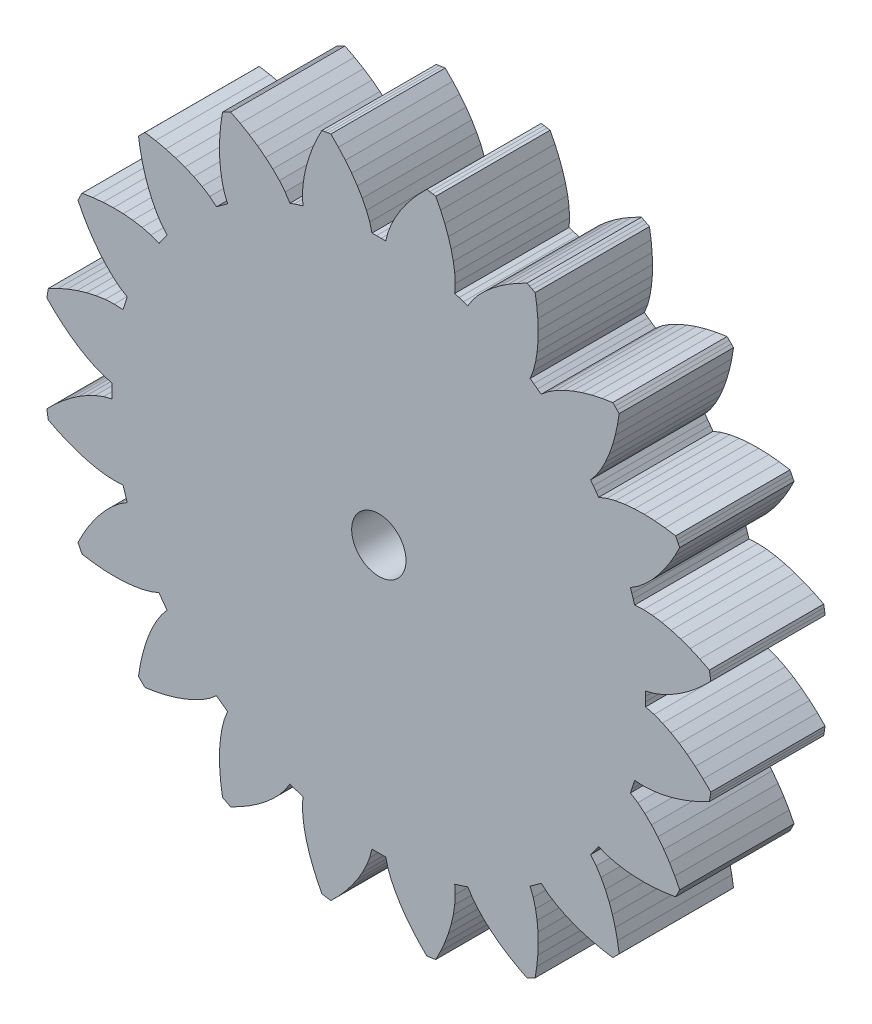
SolidWorks part; units mm, degrees
ref_plane "前视基准面" through (0, 0, 0) normal (0, 0, 1) x (1, 0, 0)
ref_plane "上视基准面" through (0, 0, 0) normal (0, 1, 0) x (1, 0, 0)
ref_plane "右视基准面" through (0, 0, 0) normal (1, 0, 0) x (0, 0, -1)
other "Configuration Table"
sketch "草图1" plane through (0, 0, 0) normal (0, 0, 1) x (1, 0, 0)
  line L0 (34.9884, 0.9021) -> (36.1053, 1.1916)
  line L1 (36.1053, 1.1916) -> (37.2145, 1.6253)
  line L2 (37.2145, 1.6253) -> (38.3134, 2.1726)
  line L3 (38.3134, 2.1726) -> (39.3992, 2.8203)
  line L4 (39.3992, 2.8203) -> (40.4686, 3.5609)
  line L5 (40.4686, 3.5609) -> (41.5186, 4.3893)
  line L6 (41.5186, 4.3893) -> (42.546, 5.3016)
  line L7 (42.546, 5.3016) -> (43.5474, 6.2949)
  line L8 (43.5474, 6.2949) -> (43.4889, 6.6872)
  line L9 (43.4889, 6.6872) -> (43.4268, 7.0789)
  line L10 (43.4268, 7.0789) -> (43.3613, 7.4701)
  line L11 (43.3613, 7.4701) -> (42.1019, 8.1053)
  line L12 (42.1019, 8.1053) -> (40.8429, 8.6555)
  line L13 (40.8429, 8.6555) -> (39.5883, 9.1189)
  line L14 (39.5883, 9.1189) -> (38.3424, 9.4927)
  line L15 (38.3424, 9.4927) -> (37.1096, 9.7732)
  line L16 (37.1096, 9.7732) -> (35.8954, 9.9541)
  line L17 (35.8954, 9.9541) -> (34.7064, 10.0239)
  line L18 (34.7064, 10.0239) -> (33.5547, 9.954)
  line L19 (33.5547, 9.954) -> (33.3787, 10.5292)
  line L20 (33.3787, 10.5292) -> (33.1928, 11.1012)
  line L21 (33.1928, 11.1012) -> (32.9971, 11.67)
  line L22 (32.9971, 11.67) -> (33.97, 12.2904)
  line L23 (33.97, 12.2904) -> (34.8909, 13.0457)
  line L24 (34.8909, 13.0457) -> (35.7669, 13.9058)
  line L25 (35.7669, 13.9058) -> (36.5993, 14.8573)
  line L26 (36.5993, 14.8573) -> (37.3876, 15.8921)
  line L27 (37.3876, 15.8921) -> (38.1302, 17.0044)
  line L28 (38.1302, 17.0044) -> (38.8253, 18.1895)
  line L29 (38.8253, 18.1895) -> (39.4708, 19.4437)
  line L30 (39.4708, 19.4437) -> (39.2939, 19.7987)
  line L31 (39.2939, 19.7987) -> (39.1139, 20.1521)
  line L32 (39.1139, 20.1521) -> (38.9306, 20.5038)
  line L33 (38.9306, 20.5038) -> (37.5366, 20.7188)
  line L34 (37.5366, 20.7188) -> (36.1692, 20.8531)
  line L35 (36.1692, 20.8531) -> (34.8329, 20.906)
  line L36 (34.8329, 20.906) -> (33.5324, 20.8766)
  line L37 (33.5324, 20.8766) -> (32.2733, 20.7624)
  line L38 (32.2733, 20.7624) -> (31.0625, 20.5592)
  line L39 (31.0625, 20.5592) -> (29.9102, 20.2582)
  line L40 (29.9102, 20.2582) -> (28.8365, 19.8358)
  line L41 (28.8365, 19.8358) -> (28.4913, 20.3284)
  line L42 (28.4913, 20.3284) -> (28.1378, 20.815)
  line L43 (28.1378, 20.815) -> (27.7759, 21.2955)
  line L44 (27.7759, 21.2955) -> (28.5094, 22.1862)
  line L45 (28.5094, 22.1862) -> (29.1518, 23.1891)
  line L46 (29.1518, 23.1891) -> (29.7192, 24.2778)
  line L47 (29.7192, 24.2778) -> (30.2169, 25.44)
  line L48 (30.2169, 25.44) -> (30.6468, 26.6677)
  line L49 (30.6468, 26.6677) -> (31.0093, 27.955)
  line L50 (31.0093, 27.955) -> (31.3042, 29.297)
  line L51 (31.3042, 29.297) -> (31.5305, 30.6892)
  line L52 (31.5305, 30.6892) -> (31.2526, 30.9722)
  line L53 (31.2526, 30.9722) -> (30.9722, 31.2526)
  line L54 (30.9722, 31.2526) -> (30.6892, 31.5305)
  line L55 (30.6892, 31.5305) -> (29.297, 31.3042)
  line L56 (29.297, 31.3042) -> (27.955, 31.0093)
  line L57 (27.955, 31.0093) -> (26.6677, 30.6468)
  line L58 (26.6677, 30.6468) -> (25.44, 30.2169)
  line L59 (25.44, 30.2169) -> (24.2778, 29.7192)
  line L60 (24.2778, 29.7192) -> (23.1891, 29.1518)
  line L61 (23.1891, 29.1518) -> (22.1862, 28.5094)
  line L62 (22.1862, 28.5094) -> (21.2955, 27.7759)
  line L63 (21.2955, 27.7759) -> (20.815, 28.1378)
  line L64 (20.815, 28.1378) -> (20.3284, 28.4913)
  line L65 (20.3284, 28.4913) -> (19.8358, 28.8365)
  line L66 (19.8358, 28.8365) -> (20.2582, 29.9102)
  line L67 (20.2582, 29.9102) -> (20.5592, 31.0625)
  line L68 (20.5592, 31.0625) -> (20.7624, 32.2733)
  line L69 (20.7624, 32.2733) -> (20.8766, 33.5324)
  line L70 (20.8766, 33.5324) -> (20.906, 34.8329)
  line L71 (20.906, 34.8329) -> (20.8531, 36.1692)
  line L72 (20.8531, 36.1692) -> (20.7188, 37.5366)
  line L73 (20.7188, 37.5366) -> (20.5038, 38.9306)
  line L74 (20.5038, 38.9306) -> (20.1521, 39.1139)
  line L75 (20.1521, 39.1139) -> (19.7987, 39.2939)
  line L76 (19.7987, 39.2939) -> (19.4437, 39.4708)
  line L77 (19.4437, 39.4708) -> (18.1895, 38.8253)
  line L78 (18.1895, 38.8253) -> (17.0044, 38.1302)
  line L79 (17.0044, 38.1302) -> (15.8921, 37.3876)
  line L80 (15.8921, 37.3876) -> (14.8573, 36.5993)
  line L81 (14.8573, 36.5993) -> (13.9058, 35.7669)
  line L82 (13.9058, 35.7669) -> (13.0457, 34.8909)
  line L83 (13.0457, 34.8909) -> (12.2904, 33.97)
  line L84 (12.2904, 33.97) -> (11.67, 32.9971)
  line L85 (11.67, 32.9971) -> (11.1012, 33.1928)
  line L86 (11.1012, 33.1928) -> (10.5292, 33.3787)
  line L87 (10.5292, 33.3787) -> (9.954, 33.5547)
  line L88 (9.954, 33.5547) -> (10.0239, 34.7064)
  line L89 (10.0239, 34.7064) -> (9.9541, 35.8954)
  line L90 (9.9541, 35.8954) -> (9.7732, 37.1096)
  line L91 (9.7732, 37.1096) -> (9.4927, 38.3424)
  line L92 (9.4927, 38.3424) -> (9.1189, 39.5883)
  line L93 (9.1189, 39.5883) -> (8.6555, 40.8429)
  line L94 (8.6555, 40.8429) -> (8.1053, 42.1019)
  line L95 (8.1053, 42.1019) -> (7.4701, 43.3613)
  line L96 (7.4701, 43.3613) -> (7.0789, 43.4268)
  line L97 (7.0789, 43.4268) -> (6.6872, 43.4889)
  line L98 (6.6872, 43.4889) -> (6.2949, 43.5474)
  line L99 (6.2949, 43.5474) -> (5.3016, 42.546)
  line L100 (5.3016, 42.546) -> (4.3893, 41.5186)
  line L101 (4.3893, 41.5186) -> (3.5609, 40.4686)
  line L102 (3.5609, 40.4686) -> (2.8203, 39.3992)
  line L103 (2.8203, 39.3992) -> (2.1726, 38.3134)
  line L104 (2.1726, 38.3134) -> (1.6253, 37.2145)
  line L105 (1.6253, 37.2145) -> (1.1916, 36.1053)
  line L106 (1.1916, 36.1053) -> (0.9021, 34.9884)
  line L107 (0.9021, 34.9884) -> (0.3007, 34.9987)
  line L108 (0.3007, 34.9987) -> (-0.3007, 34.9987)
  line L109 (-0.3007, 34.9987) -> (-0.9021, 34.9884)
  line L110 (-0.9021, 34.9884) -> (-1.1916, 36.1053)
  line L111 (-1.1916, 36.1053) -> (-1.6253, 37.2145)
  line L112 (-1.6253, 37.2145) -> (-2.1726, 38.3134)
  line L113 (-2.1726, 38.3134) -> (-2.8203, 39.3992)
  line L114 (-2.8203, 39.3992) -> (-3.5609, 40.4686)
  line L115 (-3.5609, 40.4686) -> (-4.3893, 41.5186)
  line L116 (-4.3893, 41.5186) -> (-5.3016, 42.546)
  line L117 (-5.3016, 42.546) -> (-6.2949, 43.5474)
  line L118 (-6.2949, 43.5474) -> (-6.6872, 43.4889)
  line L119 (-6.6872, 43.4889) -> (-7.0789, 43.4268)
  line L120 (-7.0789, 43.4268) -> (-7.4701, 43.3613)
  line L121 (-7.4701, 43.3613) -> (-8.1053, 42.1019)
  line L122 (-8.1053, 42.1019) -> (-8.6555, 40.8429)
  line L123 (-8.6555, 40.8429) -> (-9.1189, 39.5883)
  line L124 (-9.1189, 39.5883) -> (-9.4927, 38.3424)
  line L125 (-9.4927, 38.3424) -> (-9.7732, 37.1096)
  line L126 (-9.7732, 37.1096) -> (-9.9541, 35.8954)
  line L127 (-9.9541, 35.8954) -> (-10.0239, 34.7064)
  line L128 (-10.0239, 34.7064) -> (-9.954, 33.5547)
  line L129 (-9.954, 33.5547) -> (-10.5292, 33.3787)
  line L130 (-10.5292, 33.3787) -> (-11.1012, 33.1928)
  line L131 (-11.1012, 33.1928) -> (-11.67, 32.9971)
  line L132 (-11.67, 32.9971) -> (-12.2904, 33.97)
  line L133 (-12.2904, 33.97) -> (-13.0457, 34.8909)
  line L134 (-13.0457, 34.8909) -> (-13.9058, 35.7669)
  line L135 (-13.9058, 35.7669) -> (-14.8573, 36.5993)
  line L136 (-14.8573, 36.5993) -> (-15.8921, 37.3876)
  line L137 (-15.8921, 37.3876) -> (-17.0044, 38.1302)
  line L138 (-17.0044, 38.1302) -> (-18.1895, 38.8253)
  line L139 (-18.1895, 38.8253) -> (-19.4437, 39.4708)
  line L140 (-19.4437, 39.4708) -> (-19.7987, 39.2939)
  line L141 (-19.7987, 39.2939) -> (-20.1521, 39.1139)
  line L142 (-20.1521, 39.1139) -> (-20.5038, 38.9306)
  line L143 (-20.5038, 38.9306) -> (-20.7188, 37.5366)
  line L144 (-20.7188, 37.5366) -> (-20.8531, 36.1692)
  line L145 (-20.8531, 36.1692) -> (-20.906, 34.8329)
  line L146 (-20.906, 34.8329) -> (-20.8766, 33.5324)
  line L147 (-20.8766, 33.5324) -> (-20.7624, 32.2733)
  line L148 (-20.7624, 32.2733) -> (-20.5592, 31.0625)
  line L149 (-20.5592, 31.0625) -> (-20.2582, 29.9102)
  line L150 (-20.2582, 29.9102) -> (-19.8358, 28.8365)
  line L151 (-19.8358, 28.8365) -> (-20.3284, 28.4913)
  line L152 (-20.3284, 28.4913) -> (-20.815, 28.1378)
  line L153 (-20.815, 28.1378) -> (-21.2955, 27.7759)
  line L154 (-21.2955, 27.7759) -> (-22.1862, 28.5094)
  line L155 (-22.1862, 28.5094) -> (-23.1891, 29.1518)
  line L156 (-23.1891, 29.1518) -> (-24.2778, 29.7192)
  line L157 (-24.2778, 29.7192) -> (-25.44, 30.2169)
  line L158 (-25.44, 30.2169) -> (-26.6677, 30.6468)
  line L159 (-26.6677, 30.6468) -> (-27.955, 31.0093)
  line L160 (-27.955, 31.0093) -> (-29.297, 31.3042)
  line L161 (-29.297, 31.3042) -> (-30.6892, 31.5305)
  line L162 (-30.6892, 31.5305) -> (-30.9722, 31.2526)
  line L163 (-30.9722, 31.2526) -> (-31.2526, 30.9722)
  line L164 (-31.2526, 30.9722) -> (-31.5305, 30.6892)
  line L165 (-31.5305, 30.6892) -> (-31.3042, 29.297)
  line L166 (-31.3042, 29.297) -> (-31.0093, 27.955)
  line L167 (-31.0093, 27.955) -> (-30.6468, 26.6677)
  line L168 (-30.6468, 26.6677) -> (-30.2169, 25.44)
  line L169 (-30.2169, 25.44) -> (-29.7192, 24.2778)
  line L170 (-29.7192, 24.2778) -> (-29.1518, 23.1891)
  line L171 (-29.1518, 23.1891) -> (-28.5094, 22.1862)
  line L172 (-28.5094, 22.1862) -> (-27.7759, 21.2955)
  line L173 (-27.7759, 21.2955) -> (-28.1378, 20.815)
  line L174 (-28.1378, 20.815) -> (-28.4913, 20.3284)
  line L175 (-28.4913, 20.3284) -> (-28.8365, 19.8358)
  line L176 (-28.8365, 19.8358) -> (-29.9102, 20.2582)
  line L177 (-29.9102, 20.2582) -> (-31.0625, 20.5592)
  line L178 (-31.0625, 20.5592) -> (-32.2733, 20.7624)
  line L179 (-32.2733, 20.7624) -> (-33.5324, 20.8766)
  line L180 (-33.5324, 20.8766) -> (-34.8329, 20.906)
  line L181 (-34.8329, 20.906) -> (-36.1692, 20.8531)
  line L182 (-36.1692, 20.8531) -> (-37.5366, 20.7188)
  line L183 (-37.5366, 20.7188) -> (-38.9306, 20.5038)
  line L184 (-38.9306, 20.5038) -> (-39.1139, 20.1521)
  line L185 (-39.1139, 20.1521) -> (-39.2939, 19.7987)
  line L186 (-39.2939, 19.7987) -> (-39.4708, 19.4437)
  line L187 (-39.4708, 19.4437) -> (-38.8253, 18.1895)
  line L188 (-38.8253, 18.1895) -> (-38.1302, 17.0044)
  line L189 (-38.1302, 17.0044) -> (-37.3876, 15.8921)
  line L190 (-37.3876, 15.8921) -> (-36.5993, 14.8573)
  line L191 (-36.5993, 14.8573) -> (-35.7669, 13.9058)
  line L192 (-35.7669, 13.9058) -> (-34.8909, 13.0457)
  line L193 (-34.8909, 13.0457) -> (-33.97, 12.2904)
  line L194 (-33.97, 12.2904) -> (-32.9971, 11.67)
  line L195 (-32.9971, 11.67) -> (-33.1928, 11.1012)
  line L196 (-33.1928, 11.1012) -> (-33.3787, 10.5292)
  line L197 (-33.3787, 10.5292) -> (-33.5547, 9.954)
  line L198 (-33.5547, 9.954) -> (-34.7064, 10.0239)
  line L199 (-34.7064, 10.0239) -> (-35.8954, 9.9541)
  line L200 (-35.8954, 9.9541) -> (-37.1096, 9.7732)
  line L201 (-37.1096, 9.7732) -> (-38.3424, 9.4927)
  line L202 (-38.3424, 9.4927) -> (-39.5883, 9.1189)
  line L203 (-39.5883, 9.1189) -> (-40.8429, 8.6555)
  line L204 (-40.8429, 8.6555) -> (-42.1019, 8.1053)
  line L205 (-42.1019, 8.1053) -> (-43.3613, 7.4701)
  line L206 (-43.3613, 7.4701) -> (-43.4268, 7.0789)
  line L207 (-43.4268, 7.0789) -> (-43.4889, 6.6872)
  line L208 (-43.4889, 6.6872) -> (-43.5474, 6.2949)
  line L209 (-43.5474, 6.2949) -> (-42.546, 5.3016)
  line L210 (-42.546, 5.3016) -> (-41.5186, 4.3893)
  line L211 (-41.5186, 4.3893) -> (-40.4686, 3.5609)
  line L212 (-40.4686, 3.5609) -> (-39.3992, 2.8203)
  line L213 (-39.3992, 2.8203) -> (-38.3134, 2.1726)
  line L214 (-38.3134, 2.1726) -> (-37.2145, 1.6253)
  line L215 (-37.2145, 1.6253) -> (-36.1053, 1.1916)
  line L216 (-36.1053, 1.1916) -> (-34.9884, 0.9021)
  line L217 (-34.9884, 0.9021) -> (-34.9987, 0.3007)
  line L218 (-34.9987, 0.3007) -> (-34.9987, -0.3007)
  line L219 (-34.9987, -0.3007) -> (-34.9884, -0.9021)
  line L220 (-34.9884, -0.9021) -> (-36.1053, -1.1916)
  line L221 (-36.1053, -1.1916) -> (-37.2145, -1.6253)
  line L222 (-37.2145, -1.6253) -> (-38.3134, -2.1726)
  line L223 (-38.3134, -2.1726) -> (-39.3992, -2.8203)
  line L224 (-39.3992, -2.8203) -> (-40.4686, -3.5609)
  line L225 (-40.4686, -3.5609) -> (-41.5186, -4.3893)
  line L226 (-41.5186, -4.3893) -> (-42.546, -5.3016)
  line L227 (-42.546, -5.3016) -> (-43.5474, -6.2949)
  line L228 (-43.5474, -6.2949) -> (-43.4889, -6.6872)
  line L229 (-43.4889, -6.6872) -> (-43.4268, -7.0789)
  line L230 (-43.4268, -7.0789) -> (-43.3613, -7.4701)
  line L231 (-43.3613, -7.4701) -> (-42.1019, -8.1053)
  line L232 (-42.1019, -8.1053) -> (-40.8429, -8.6555)
  line L233 (-40.8429, -8.6555) -> (-39.5883, -9.1189)
  line L234 (-39.5883, -9.1189) -> (-38.3424, -9.4927)
  line L235 (-38.3424, -9.4927) -> (-37.1096, -9.7732)
  line L236 (-37.1096, -9.7732) -> (-35.8954, -9.9541)
  line L237 (-35.8954, -9.9541) -> (-34.7064, -10.0239)
  line L238 (-34.7064, -10.0239) -> (-33.5547, -9.954)
  line L239 (-33.5547, -9.954) -> (-33.3787, -10.5292)
  line L240 (-33.3787, -10.5292) -> (-33.1928, -11.1012)
  line L241 (-33.1928, -11.1012) -> (-32.9971, -11.67)
  line L242 (-32.9971, -11.67) -> (-33.97, -12.2904)
  line L243 (-33.97, -12.2904) -> (-34.8909, -13.0457)
  line L244 (-34.8909, -13.0457) -> (-35.7669, -13.9058)
  line L245 (-35.7669, -13.9058) -> (-36.5993, -14.8573)
  line L246 (-36.5993, -14.8573) -> (-37.3876, -15.8921)
  line L247 (-37.3876, -15.8921) -> (-38.1302, -17.0044)
  line L248 (-38.1302, -17.0044) -> (-38.8253, -18.1895)
  line L249 (-38.8253, -18.1895) -> (-39.4708, -19.4437)
  line L250 (-39.4708, -19.4437) -> (-39.2939, -19.7987)
  line L251 (-39.2939, -19.7987) -> (-39.1139, -20.1521)
  line L252 (-39.1139, -20.1521) -> (-38.9306, -20.5038)
  line L253 (-38.9306, -20.5038) -> (-37.5366, -20.7188)
  line L254 (-37.5366, -20.7188) -> (-36.1692, -20.8531)
  line L255 (-36.1692, -20.8531) -> (-34.8329, -20.906)
  line L256 (-34.8329, -20.906) -> (-33.5324, -20.8766)
  line L257 (-33.5324, -20.8766) -> (-32.2733, -20.7624)
  line L258 (-32.2733, -20.7624) -> (-31.0625, -20.5592)
  line L259 (-31.0625, -20.5592) -> (-29.9102, -20.2582)
  line L260 (-29.9102, -20.2582) -> (-28.8365, -19.8358)
  line L261 (-28.8365, -19.8358) -> (-28.4913, -20.3284)
  line L262 (-28.4913, -20.3284) -> (-28.1378, -20.815)
  line L263 (-28.1378, -20.815) -> (-27.7759, -21.2955)
  line L264 (-27.7759, -21.2955) -> (-28.5094, -22.1862)
  line L265 (-28.5094, -22.1862) -> (-29.1518, -23.1891)
  line L266 (-29.1518, -23.1891) -> (-29.7192, -24.2778)
  line L267 (-29.7192, -24.2778) -> (-30.2169, -25.44)
  line L268 (-30.2169, -25.44) -> (-30.6468, -26.6677)
  line L269 (-30.6468, -26.6677) -> (-31.0093, -27.955)
  line L270 (-31.0093, -27.955) -> (-31.3042, -29.297)
  line L271 (-31.3042, -29.297) -> (-31.5305, -30.6892)
  line L272 (-31.5305, -30.6892) -> (-31.2526, -30.9722)
  line L273 (-31.2526, -30.9722) -> (-30.9722, -31.2526)
  line L274 (-30.9722, -31.2526) -> (-30.6892, -31.5305)
  line L275 (-30.6892, -31.5305) -> (-29.297, -31.3042)
  line L276 (-29.297, -31.3042) -> (-27.955, -31.0093)
  line L277 (-27.955, -31.0093) -> (-26.6677, -30.6468)
  line L278 (-26.6677, -30.6468) -> (-25.44, -30.2169)
  line L279 (-25.44, -30.2169) -> (-24.2778, -29.7192)
  line L280 (-24.2778, -29.7192) -> (-23.1891, -29.1518)
  line L281 (-23.1891, -29.1518) -> (-22.1862, -28.5094)
  line L282 (-22.1862, -28.5094) -> (-21.2955, -27.7759)
  line L283 (-21.2955, -27.7759) -> (-20.815, -28.1378)
  line L284 (-20.815, -28.1378) -> (-20.3284, -28.4913)
  line L285 (-20.3284, -28.4913) -> (-19.8358, -28.8365)
  line L286 (-19.8358, -28.8365) -> (-20.2582, -29.9102)
  line L287 (-20.2582, -29.9102) -> (-20.5592, -31.0625)
  line L288 (-20.5592, -31.0625) -> (-20.7624, -32.2733)
  line L289 (-20.7624, -32.2733) -> (-20.8766, -33.5324)
  line L290 (-20.8766, -33.5324) -> (-20.906, -34.8329)
  line L291 (-20.906, -34.8329) -> (-20.8531, -36.1692)
  line L292 (-20.8531, -36.1692) -> (-20.7188, -37.5366)
  line L293 (-20.7188, -37.5366) -> (-20.5038, -38.9306)
  line L294 (-20.5038, -38.9306) -> (-20.1521, -39.1139)
  line L295 (-20.1521, -39.1139) -> (-19.7987, -39.2939)
  line L296 (-19.7987, -39.2939) -> (-19.4437, -39.4708)
  line L297 (-19.4437, -39.4708) -> (-18.1895, -38.8253)
  line L298 (-18.1895, -38.8253) -> (-17.0044, -38.1302)
  line L299 (-17.0044, -38.1302) -> (-15.8921, -37.3876)
  line L300 (-15.8921, -37.3876) -> (-14.8573, -36.5993)
  line L301 (-14.8573, -36.5993) -> (-13.9058, -35.7669)
  line L302 (-13.9058, -35.7669) -> (-13.0457, -34.8909)
  line L303 (-13.0457, -34.8909) -> (-12.2904, -33.97)
  line L304 (-12.2904, -33.97) -> (-11.67, -32.9971)
  line L305 (-11.67, -32.9971) -> (-11.1012, -33.1928)
  line L306 (-11.1012, -33.1928) -> (-10.5292, -33.3787)
  line L307 (-10.5292, -33.3787) -> (-9.954, -33.5547)
  line L308 (-9.954, -33.5547) -> (-10.0239, -34.7064)
  line L309 (-10.0239, -34.7064) -> (-9.9541, -35.8954)
  line L310 (-9.9541, -35.8954) -> (-9.7732, -37.1096)
  line L311 (-9.7732, -37.1096) -> (-9.4927, -38.3424)
  line L312 (-9.4927, -38.3424) -> (-9.1189, -39.5883)
  line L313 (-9.1189, -39.5883) -> (-8.6555, -40.8429)
  line L314 (-8.6555, -40.8429) -> (-8.1053, -42.1019)
  line L315 (-8.1053, -42.1019) -> (-7.4701, -43.3613)
  line L316 (-7.4701, -43.3613) -> (-7.0789, -43.4268)
  line L317 (-7.0789, -43.4268) -> (-6.6872, -43.4889)
  line L318 (-6.6872, -43.4889) -> (-6.2949, -43.5474)
  line L319 (-6.2949, -43.5474) -> (-5.3016, -42.546)
  line L320 (-5.3016, -42.546) -> (-4.3893, -41.5186)
  line L321 (-4.3893, -41.5186) -> (-3.5609, -40.4686)
  line L322 (-3.5609, -40.4686) -> (-2.8203, -39.3992)
  line L323 (-2.8203, -39.3992) -> (-2.1726, -38.3134)
  line L324 (-2.1726, -38.3134) -> (-1.6253, -37.2145)
  line L325 (-1.6253, -37.2145) -> (-1.1916, -36.1053)
  line L326 (-1.1916, -36.1053) -> (-0.9021, -34.9884)
  line L327 (-0.9021, -34.9884) -> (-0.3007, -34.9987)
  line L328 (-0.3007, -34.9987) -> (0.3007, -34.9987)
  line L329 (0.3007, -34.9987) -> (0.9021, -34.9884)
  line L330 (0.9021, -34.9884) -> (1.1916, -36.1053)
  line L331 (1.1916, -36.1053) -> (1.6253, -37.2145)
  line L332 (1.6253, -37.2145) -> (2.1726, -38.3134)
  line L333 (2.1726, -38.3134) -> (2.8203, -39.3992)
  line L334 (2.8203, -39.3992) -> (3.5609, -40.4686)
  line L335 (3.5609, -40.4686) -> (4.3893, -41.5186)
  line L336 (4.3893, -41.5186) -> (5.3016, -42.546)
  line L337 (5.3016, -42.546) -> (6.2949, -43.5474)
  line L338 (6.2949, -43.5474) -> (6.6872, -43.4889)
  line L339 (6.6872, -43.4889) -> (7.0789, -43.4268)
  line L340 (7.0789, -43.4268) -> (7.4701, -43.3613)
  line L341 (7.4701, -43.3613) -> (8.1053, -42.1019)
  line L342 (8.1053, -42.1019) -> (8.6555, -40.8429)
  line L343 (8.6555, -40.8429) -> (9.1189, -39.5883)
  line L344 (9.1189, -39.5883) -> (9.4927, -38.3424)
  line L345 (9.4927, -38.3424) -> (9.7732, -37.1096)
  line L346 (9.7732, -37.1096) -> (9.9541, -35.8954)
  line L347 (9.9541, -35.8954) -> (10.0239, -34.7064)
  line L348 (10.0239, -34.7064) -> (9.954, -33.5547)
  line L349 (9.954, -33.5547) -> (10.5292, -33.3787)
  line L350 (10.5292, -33.3787) -> (11.1012, -33.1928)
  line L351 (11.1012, -33.1928) -> (11.67, -32.9971)
  line L352 (11.67, -32.9971) -> (12.2904, -33.97)
  line L353 (12.2904, -33.97) -> (13.0457, -34.8909)
  line L354 (13.0457, -34.8909) -> (13.9058, -35.7669)
  line L355 (13.9058, -35.7669) -> (14.8573, -36.5993)
  line L356 (14.8573, -36.5993) -> (15.8921, -37.3876)
  line L357 (15.8921, -37.3876) -> (17.0044, -38.1302)
  line L358 (17.0044, -38.1302) -> (18.1895, -38.8253)
  line L359 (18.1895, -38.8253) -> (19.4437, -39.4708)
  line L360 (19.4437, -39.4708) -> (19.7987, -39.2939)
  line L361 (19.7987, -39.2939) -> (20.1521, -39.1139)
  line L362 (20.1521, -39.1139) -> (20.5038, -38.9306)
  line L363 (20.5038, -38.9306) -> (20.7188, -37.5366)
  line L364 (20.7188, -37.5366) -> (20.8531, -36.1692)
  line L365 (20.8531, -36.1692) -> (20.906, -34.8329)
  line L366 (20.906, -34.8329) -> (20.8766, -33.5324)
  line L367 (20.8766, -33.5324) -> (20.7624, -32.2733)
  line L368 (20.7624, -32.2733) -> (20.5592, -31.0625)
  line L369 (20.5592, -31.0625) -> (20.2582, -29.9102)
  line L370 (20.2582, -29.9102) -> (19.8358, -28.8365)
  line L371 (19.8358, -28.8365) -> (20.3284, -28.4913)
  line L372 (20.3284, -28.4913) -> (20.815, -28.1378)
  line L373 (20.815, -28.1378) -> (21.2955, -27.7759)
  line L374 (21.2955, -27.7759) -> (22.1862, -28.5094)
  line L375 (22.1862, -28.5094) -> (23.1891, -29.1518)
  line L376 (23.1891, -29.1518) -> (24.2778, -29.7192)
  line L377 (24.2778, -29.7192) -> (25.44, -30.2169)
  line L378 (25.44, -30.2169) -> (26.6677, -30.6468)
  line L379 (26.6677, -30.6468) -> (27.955, -31.0093)
  line L380 (27.955, -31.0093) -> (29.297, -31.3042)
  line L381 (29.297, -31.3042) -> (30.6892, -31.5305)
  line L382 (30.6892, -31.5305) -> (30.9722, -31.2526)
  line L383 (30.9722, -31.2526) -> (31.2526, -30.9722)
  line L384 (31.2526, -30.9722) -> (31.5305, -30.6892)
  line L385 (31.5305, -30.6892) -> (31.3042, -29.297)
  line L386 (31.3042, -29.297) -> (31.0093, -27.955)
  line L387 (31.0093, -27.955) -> (30.6468, -26.6677)
  line L388 (30.6468, -26.6677) -> (30.2169, -25.44)
  line L389 (30.2169, -25.44) -> (29.7192, -24.2778)
  line L390 (29.7192, -24.2778) -> (29.1518, -23.1891)
  line L391 (29.1518, -23.1891) -> (28.5094, -22.1862)
  line L392 (28.5094, -22.1862) -> (27.7759, -21.2955)
  line L393 (27.7759, -21.2955) -> (28.1378, -20.815)
  line L394 (28.1378, -20.815) -> (28.4913, -20.3284)
  line L395 (28.4913, -20.3284) -> (28.8365, -19.8358)
  line L396 (28.8365, -19.8358) -> (29.9102, -20.2582)
  line L397 (29.9102, -20.2582) -> (31.0625, -20.5592)
  line L398 (31.0625, -20.5592) -> (32.2733, -20.7624)
  line L399 (32.2733, -20.7624) -> (33.5324, -20.8766)
  line L400 (33.5324, -20.8766) -> (34.8329, -20.906)
  line L401 (34.8329, -20.906) -> (36.1692, -20.8531)
  line L402 (36.1692, -20.8531) -> (37.5366, -20.7188)
  line L403 (37.5366, -20.7188) -> (38.9306, -20.5038)
  line L404 (38.9306, -20.5038) -> (39.1139, -20.1521)
  line L405 (39.1139, -20.1521) -> (39.2939, -19.7987)
  line L406 (39.2939, -19.7987) -> (39.4708, -19.4437)
  line L407 (39.4708, -19.4437) -> (38.8253, -18.1895)
  line L408 (38.8253, -18.1895) -> (38.1302, -17.0044)
  line L409 (38.1302, -17.0044) -> (37.3876, -15.8921)
  line L410 (37.3876, -15.8921) -> (36.5993, -14.8573)
  line L411 (36.5993, -14.8573) -> (35.7669, -13.9058)
  line L412 (35.7669, -13.9058) -> (34.8909, -13.0457)
  line L413 (34.8909, -13.0457) -> (33.97, -12.2904)
  line L414 (33.97, -12.2904) -> (32.9971, -11.67)
  line L415 (32.9971, -11.67) -> (33.1928, -11.1012)
  line L416 (33.1928, -11.1012) -> (33.3787, -10.5292)
  line L417 (33.3787, -10.5292) -> (33.5547, -9.954)
  line L418 (33.5547, -9.954) -> (34.7064, -10.0239)
  line L419 (34.7064, -10.0239) -> (35.8954, -9.9541)
  line L420 (35.8954, -9.9541) -> (37.1096, -9.7732)
  line L421 (37.1096, -9.7732) -> (38.3424, -9.4927)
  line L422 (38.3424, -9.4927) -> (39.5883, -9.1189)
  line L423 (39.5883, -9.1189) -> (40.8429, -8.6555)
  line L424 (40.8429, -8.6555) -> (42.1019, -8.1053)
  line L425 (42.1019, -8.1053) -> (43.3613, -7.4701)
  line L426 (43.3613, -7.4701) -> (43.4268, -7.0789)
  line L427 (43.4268, -7.0789) -> (43.4889, -6.6872)
  line L428 (43.4889, -6.6872) -> (43.5474, -6.2949)
  line L429 (43.5474, -6.2949) -> (42.546, -5.3016)
  line L430 (42.546, -5.3016) -> (41.5186, -4.3893)
  line L431 (41.5186, -4.3893) -> (40.4686, -3.5609)
  line L432 (40.4686, -3.5609) -> (39.3992, -2.8203)
  line L433 (39.3992, -2.8203) -> (38.3134, -2.1726)
  line L434 (38.3134, -2.1726) -> (37.2145, -1.6253)
  line L435 (37.2145, -1.6253) -> (36.1053, -1.1916)
  line L436 (36.1053, -1.1916) -> (34.9884, -0.9021)
  line L437 (34.9884, -0.9021) -> (34.9987, -0.3007)
  line L438 (34.9987, -0.3007) -> (34.9987, 0.3007)
  line L439 (34.9987, 0.3007) -> (34.9884, 0.9021)
  circle A0 centre (0, 0) radius 3.5609
extrude "凸台-拉伸1" add sketch "草图1" along normal blind 15
